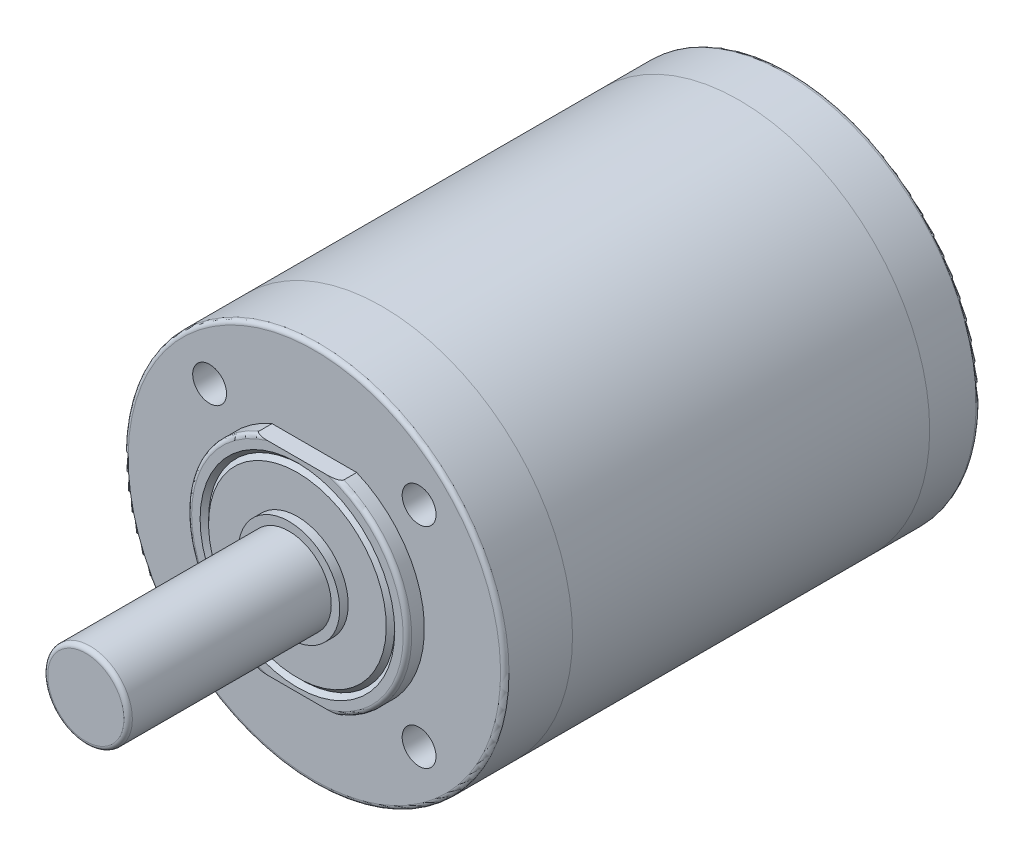
SolidWorks part; units mm, degrees
ref_plane "Front Plane" through (0, 0, 0) normal (0, 0, 1) x (1, 0, 0)
ref_plane "Top Plane" through (0, 0, 0) normal (0, 1, 0) x (1, 0, 0)
ref_plane "Right Plane" through (0, 0, 0) normal (1, 0, 0) x (0, 0, -1)
sketch "Sketch1" plane through (0, 0, 0) normal (1, 0, 0) x (0, 0, -1)
  line L0 (0, 0) -> (-83.2, 0) construction
  line L1 (0, 0) -> (0, 22.5)
  line L2 (0, 22.5) -> (-56.2, 22.5)
  line L3 (-56.2, 22.5) -> (-56.2, 13)
  line L4 (-56.2, 13) -> (-58.2, 13)
  line L5 (-58.2, 13) -> (-58.2, 11.5)
  line L6 (-59.2, 5) -> (-83.2, 5)
  line L7 (-83.2, 5) -> (-83.2, 0)
  line L8 (0, 0) -> (-83.2, 0)
  line L9 (-58.2, 11.5) -> (-57.7, 11)
  line L10 (-57.7, 11) -> (-58.2, 10.5)
  line L11 (-58.2, 6) -> (-59.2, 6)
  line L12 (-59.2, 6) -> (-59.2, 5)
  line L13 (-58.2, 10.5) -> (-58.2, 6)
  dimension "D1" = 56.2
  dimension "D2" = 22.5
  dimension "D3" = 25
  dimension "D4" = 2
  dimension "D5" = 13
  dimension "D6" = 5
  dimension "D7" = 1
  dimension "D8" = 1
  dimension "D9" = 11
  dimension "D10" = 0.5
  dimension "D11" = 135
revolve "Revolve1" add sketch "Sketch1" angle 360 about L0
sketch "Sketch2" plane through (0, 0, 0) normal (1, 0, 0) x (0, 0, -1)
  line L0 (-6, -22.5) -> (-6, 22.5)
  line L1 (-56.2, -22.5) -> (0, -22.5) construction
  line L2 (0, 22.5) -> (-56.2, 22.5) construction
  line L3 (-48.2, -22.5) -> (-48.2, 22.5)
  line L4 (-56.2, 22.5) -> (-56.2, -22.5) construction
  line L5 (0, -22.5) -> (0, 22.5) construction
  dimension "D1" = 8
  dimension "D2" = 6
split line "Split Line1"
fillet "Fillet1" radius 0.5 4 edges at (0, 22.5, 0) (0, 22.5, 56.2) (0, 13, 58.2) (0, 5, 83.2)
sketch "Sketch3" plane through (0, 0, 58.2) normal (0, 0, 1) x (1, 0, 0)
  line L0 (-5, 12) -> (5, 12)
  line L1 (0, 0) -> (-13, 0) construction
  line L2 (-5, -12) -> (5, -12)
  circle A1 centre (0, 0) radius 13 construction
  arc A2 (-5, -12) -> (5, -12) centre (0, 0) ccw
  arc A3 (5, 12) -> (-5, 12) centre (0, 0) ccw
  dimension "D1" = 24
extrude "Cut-Extrude1" cut sketch "Sketch3" against normal blind 2
sketch "Sketch4" plane through (0, 0, 56.2) normal (0, 0, 1) x (1, 0, 0)
  line L0 (-12.3744, 12.3744) -> (0, 0) construction
  line L1 (0, 0) -> (-22.5, 0) construction
  circle A0 centre (-12.3744, 12.3744) radius 2
  circle A1 centre (0, 0) radius 22.5 construction
  circle A2 centre (12.3744, 12.3744) radius 2
  circle A3 centre (12.3744, -12.3744) radius 2
  circle A4 centre (-12.3744, -12.3744) radius 2
  point P17 (0, 0)
  dimension "D2" = 4
  dimension "D1" = 45
  dimension "D3" = 17.5
  dimension "D4" = 4
extrude "Cut-Extrude2" cut sketch "Sketch4" against normal blind 8
